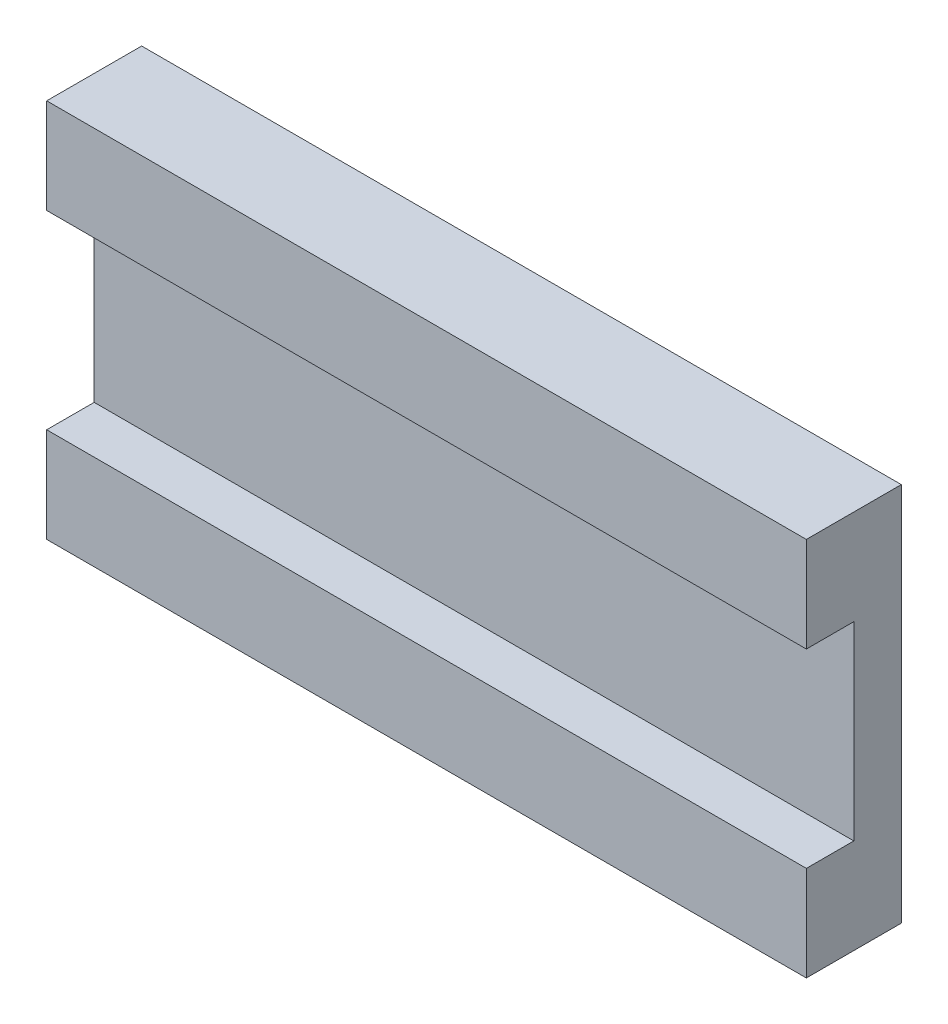
SolidWorks part; units mm, degrees
ref_plane "Front Plane" through (0, 0, 0) normal (0, 0, 1) x (1, 0, 0)
ref_plane "Top Plane" through (0, 0, 0) normal (0, 1, 0) x (1, 0, 0)
ref_plane "Right Plane" through (0, 0, 0) normal (1, 0, 0) x (0, 0, -1)
sketch "Sketch2" plane through (0, 0, 0) normal (1, 0, 0) x (0, 0, -1)
  line L0 (0, -35.0939) -> (0, 44.9061)
  line L1 (0, 44.9061) -> (-20, 44.9061)
  line L2 (-20, 44.9061) -> (-20, 24.9061)
  line L3 (-20, 24.9061) -> (-10, 24.9061)
  line L4 (-10, 24.9061) -> (-10, -15.0939)
  line L5 (-10, -15.0939) -> (-20, -15.0939)
  line L6 (-20, -15.0939) -> (-20, -35.0939)
  line L7 (-20, -35.0939) -> (0, -35.0939)
  dimension "D1" = 20
  dimension "D2" = 10
  dimension "D3" = 80
  dimension "D4" = 20
  dimension "D5" = 20
extrude "Boss-Extrude1" add sketch "Sketch2" against normal blind 160
